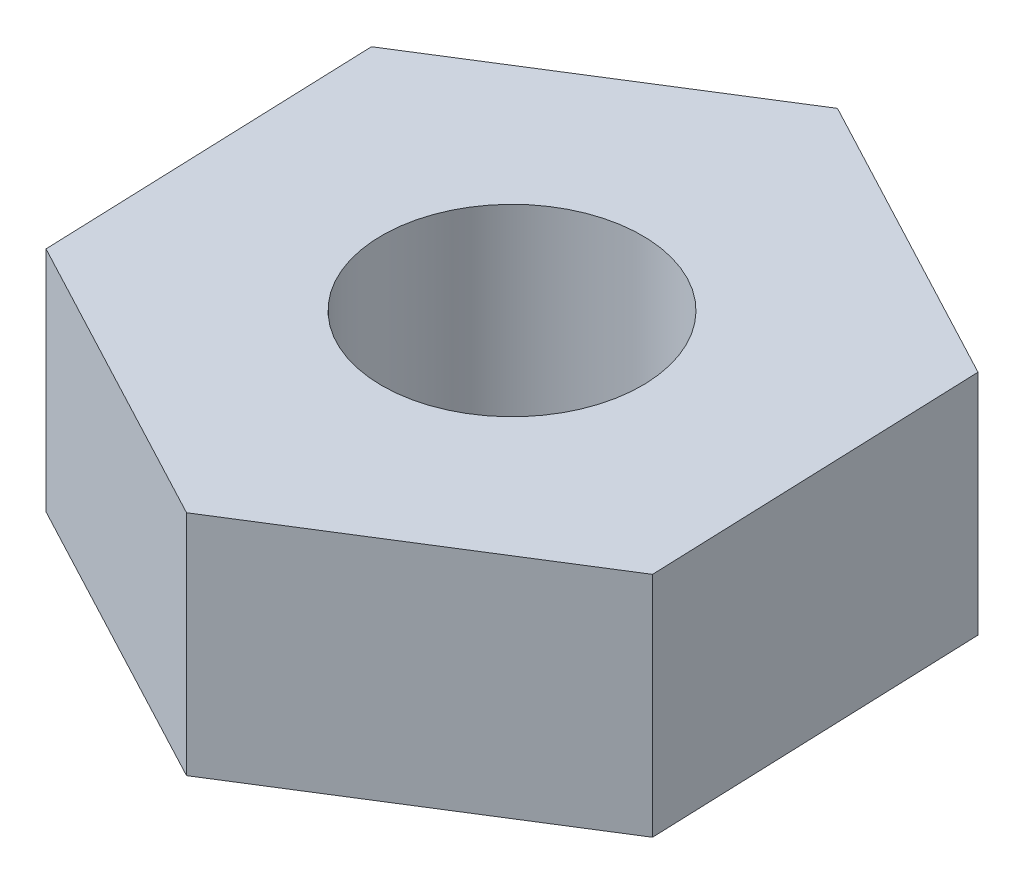
SolidWorks part; units mm, degrees
ref_plane "Front Plane" through (0, 0, 0) normal (0, 0, 1) x (1, 0, 0)
ref_plane "Top Plane" through (0, 0, 0) normal (0, 1, 0) x (1, 0, 0)
ref_plane "Right Plane" through (0, 0, 0) normal (1, 0, 0) x (0, 0, -1)
sketch "Sketch1" plane through (0, 0, 0) normal (0, 1, 0) x (1, 0, 0)
  line L1 (-0.095, 2.5963) -> (-2.296, 1.2159)
  line L2 (-2.296, 1.2159) -> (-2.201, -1.3804)
  line L3 (-2.201, -1.3804) -> (0.095, -2.5963)
  line L4 (0.095, -2.5963) -> (2.296, -1.2159)
  line L5 (2.296, -1.2159) -> (2.201, 1.3804)
  line L6 (2.201, 1.3804) -> (-0.095, 2.5963)
  circle A0 centre (0, 0) radius 1
  circle A1 centre (0, 0) radius 2.25 construction
  dimension "D1" = 2
  dimension "D2" = 4.5
extrude "Boss-Extrude1" add sketch "Sketch1" along normal blind 1.75
sketch "Sketch2" plane through (0, 1.75, 0) normal (0, 1, 0) x (1, 0, 0)
  circle A0 centre (0, 0) radius 2.25 construction
  circle A1 centre (0, 0) radius 2.25
  circle A2 centre (0, 0) radius 1 construction
  circle A3 centre (0, 0) radius 1
extrude "Boss-Extrude2" add sketch "Sketch2" against normal blind 1.75 draft 60
